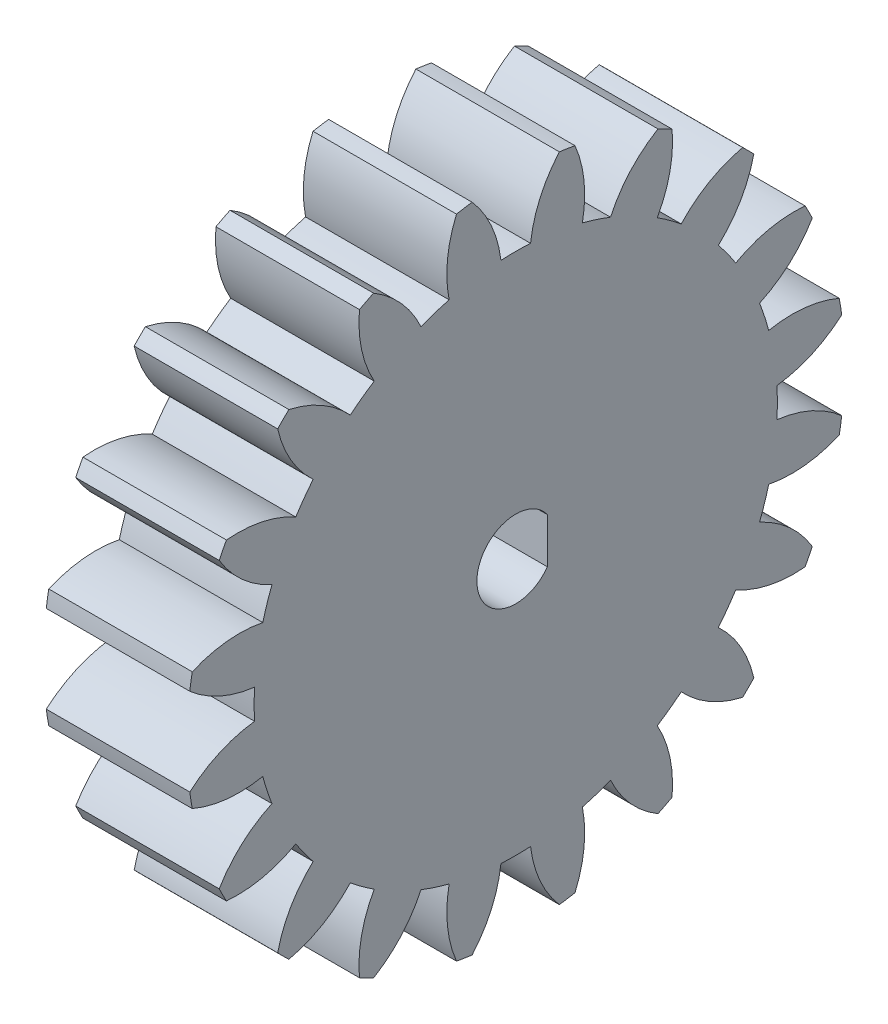
SolidWorks part; units mm, degrees
ref_plane "Plane1" through (0, 0, 0) normal (0, 0, 1) x (1, 0, 0)
ref_plane "Plane2" through (0, 0, 0) normal (0, 1, 0) x (1, 0, 0)
ref_plane "Plane3" through (0, 0, 0) normal (1, 0, 0) x (0, 0, -1)
other "Configuration Table"
sketch "HoldingSke" plane through (0, 0, 0) normal (0, 1, 0) x (1, 0, 0)
  line L0 (0, 0) -> (0.3759, -0.1368)
  line L1 (-15, 0) -> (100, 0) construction
  line L2 (0, 0) -> (-2.1039, 2.3779)
  line L3 (0, 0) -> (-11.863, 4.5341)
  line L4 (0, 0) -> (8.1152, 2.9537)
  line L5 (0, 0) -> (-46.8476, -17.4728)
  line L6 (0, 0) -> (-9.9476, -6.7116)
  line L7 (-2.1039, 2.3779) -> (8.6586, 51.2059)
  line L8 (-76.2, 54.61) -> (-76.1, 54.61)
  line L9 (-71.009, 38.7566) -> (-53.1078, 45.2721)
  line L10 (-76.2, 71.12) -> (104.1128, 71.12)
  line L11 (0, 0) -> (-12, 0)
  line L12 (-76.2, 101.6) -> (-76.113, 101.6)
  line L13 (24.9733, 27.94) -> (52.9518, 28.4284)
  line L14 (24.9733, 27.94) -> (24.9743, 27.94)
  line L15 (24.9733, 27.94) -> (100.4006, 29.5858)
  line L16 (-63.627, -2.5) -> (-12.827, -2.5)
  circle A0 centre (0, 0) radius 0.4
  circle A1 centre (0, 0) radius 21.874
  circle A2 centre (0, 0) radius 37.5
  circle A3 centre (0, 0) radius 0.4
  dimension "MHD" = 43.748
  dimension "Hub_dia" = 75
  dimension "Bore" = 0.8
  dimension "MBD" = 0.8
  dimension "Num_teeth" = 20
  dimension "Pitch" = 0.4
  dimension "Overall_len" = 50
  dimension "Show_teeth" = 20
  dimension "Thickness" = 12
  dimension "OAL" = 50.0001
  dimension "T_dim" = 0.1
  dimension "Ap" = 20
  dimension "H" = 19.05
  dimension "Pitch_radius" = 180.3128
  dimension "Width" = 12
  dimension "Backlash" = 0.087
  dimension "Addendum_fac" = 1
  dimension "Dedendum_fac" = 1.25
  dimension "Clearance_fac" = 0.25
  dimension "Dedendum_add" = 0.001
  dimension "Module" = 2.5
sketch "BasProSke" plane through (0, 0, 0) normal (0, 1, 0) x (1, 0, 0)
  line L0 (-10, 0) -> (60, 0) construction
  line L1 (0, 0) -> (0, 27.5)
  line L2 (0, 0) -> (12, 0)
  line L3 (12, 0) -> (12, 27.5)
  line L4 (12, 27.5) -> (0, 27.5)
  dimension "Thickness" = 12
  dimension "Diameter" = 55
revolve "Base-Revolve" add sketch "BasProSke" angle 360 about L0
sketch "TooCutSke" plane through (0, 0, 0) normal (1, 0, 0) x (0, 0, -1)
  line L1 (0, 0) -> (0, 107) construction
  line L2 (0, 0) -> (-2.1137, 24.9105) construction
  line L3 (0, 0) -> (-7.8012, 49.2549) construction
  line L4 (-2.1137, 24.9105) -> (-3.9006, 24.6275) construction
  arc A0 (1.2377, 21.839) -> (-1.2377, 21.839) centre (0, 0) ccw
  arc A1 (3.6672, 27.28) -> (-3.6672, 27.28) centre (0, 0) ccw
  circle A2 centre (0, 0) radius 25 construction
  circle A3 centre (0, 0) radius 23.4923 construction
  arc A4 (-1.2377, 21.839) -> (-3.6672, 27.28) centre (-11.1689, 20.6675) ccw
  arc A5 (3.6672, 27.28) -> (1.2377, 21.839) centre (11.1689, 20.6675) ccw
  dimension "Root_dia" = 43.748
  dimension "Overcut_dia" = 55.0508
  dimension "Pitch_dia" = 50
  dimension "Base_dia" = 46.9846
  dimension "Flank_rad" = 10
  dimension "Half_ang" = 9
  dimension "Half_CT" = 1.8092
extrude "ToothCut" cut sketch "TooCutSke" along normal through all
fillet "Breaks" [suppressed] radius 0.05
fillet "RootFillets" [suppressed] radius 0.626
pattern_circular "TeethCuts" count 20 every 18 about axis through (-10, 0, 0) along (1, 0, 0) of "ToothCut", "RootFillets", "Breaks"
sketch "HubNeaOneSke" plane through (0, 0, 0) normal (-1, 0, 0) x (0, 0, 1)
  circle A0 centre (0, 0) radius 21.874
  dimension "Diameter" = 43.748
extrude "HubNearOne" [suppressed] add sketch "HubNeaOneSke" along normal blind 38.0001
sketch "HubNeaBotSke" plane through (0, 0, 0) normal (-1, 0, 0) x (0, 0, 1)
  circle A0 centre (0, 0) radius 21.874
  dimension "Diameter" = 43.748
extrude "HubNearBoth" [suppressed] add sketch "HubNeaBotSke" along normal blind 19
ref_plane "FarPln" through (12, 0, 0) normal (1, 0, 0) x (0, 0, -1)
sketch "HubFarSke" plane through (12, 0, 0) normal (1, 0, 0) x (0, 0, -1)
  circle A0 centre (0, 0) radius 21.874
  dimension "Diameter" = 43.748
extrude "HubFar" [suppressed] add sketch "HubFarSke" along normal blind 19
sketch "BorSke" plane through (0, 0, 0) normal (1, 0, 0) x (0, 0, -1)
  circle A0 centre (0, 0) radius 0.4
  dimension "Diameter" = 0.8
extrude "Bore" cut sketch "BorSke" along normal mid plane 100.0001
sketch "KeySke" plane through (0, 0, 0) normal (1, 0, 0) x (0, 0, -1)
  line L0 (-0.05, 0) -> (-0.05, 0.5)
  line L1 (-0.05, 0.5) -> (0.05, 0.5)
  line L2 (0.05, 0.5) -> (0.05, 0)
  line L3 (0, 0) -> (0, 34) construction
  line L4 (-0.05, 0) -> (0.05, 0)
  dimension "Offset" = 0.5
  dimension "Width" = 0.1
extrude "Keyway" [suppressed] cut sketch "KeySke" along normal mid plane 100.0001
pattern_circular "Keyway2" [suppressed] count 2 every 90 about axis through (-10, 0, 0) along (1, 0, 0)
sketch "Çizim1" plane through (0, 0, 0) normal (-1, 0, 0) x (0, 0, 1)
  line L0 (-2.6439, 1.49) -> (-2.6439, -2.29)
  circle A0 centre (0, -0.4) radius 3.25
  circle A1 centre (0, 0) radius 0.4 construction
  dimension "D1" = 6.5
  dimension "D2" = 3.78
extrude "Kes-Ekstrüzyon1" cut sketch "Çizim1" against normal blind 100 contours L0 A0
equation "' \"Module@HoldingSke\" = 6.35"
equation "' \"Num_teeth@HoldingSke\" = 12"
equation "' \"Ap@HoldingSke\" =  20"
equation "' \"Ap@HoldingSke\" = 20"
equation "' \"Width@HoldingSke\" = 0.5 * 25.4"
equation "' \"Hub_dia@HoldingSke\"= 1 * 25.4"
equation "' \"Hub_dia@HoldingSke\" = 1 * 25.4"
equation "' \"Overall_len@HoldingSke\" = 1.0 * 25.4"
equation "' \"Bore@HoldingSke\" = 0.75 * 25.4"
equation "' \"T_dim@HoldingSke\" = 0.1 * 25.4"
equation "' \"Width@KeySke\" = 0.25 * 25.4"
equation "' \"Show_teeth@HoldingSke\" = 13"
equation "' \"Backlash@HoldingSke\" = 0.009 * 25.4"
equation "' \"Addendum_fac@HoldingSke\" = 1.0"
equation "' \"Dedendum_fac@HoldingSke\" = 1.25"
equation "' \"Dedendum_add@HoldingSke\" = 0.00005 * 25.4"
equation "' \"Clearance_fac@HoldingSke\" = 0.25"
equation "\"Pitch@HoldingSke\" = 1 / \"Module@HoldingSke\""
equation "\"Overcut_dia@TooCutSke\" = (\"Num_teeth@HoldingSke\" + 2 * \"Addendum_fac@HoldingSke\") / \"Pitch@HoldingSke\" + 0.002 * 25.4"
equation "\"Pitch_dia@TooCutSke\" = \"Num_teeth@HoldingSke\" / \"Pitch@HoldingSke\""
equation "\"Base_dia@TooCutSke\" = \"Num_teeth@HoldingSke\" / \"Pitch@HoldingSke\" * cos((\"Ap@HoldingSke\"  * 3.14159265 / 180))"
equation "\"Root_dia@TooCutSke\" = (\"Num_teeth@HoldingSke\" + 2) / \"Pitch@HoldingSke\" - 2 * (\"Addendum_fac@HoldingSke\" + \"Dedendum_fac@HoldingSke\") / \"Pitch@HoldingSke\" - \"Dedendum_add@HoldingSke\" * 2"
equation "\"Half_ang@TooCutSke\" = 180 / \"Num_teeth@HoldingSke\""
equation "\"Half_CT@TooCutSke\" = \"Num_teeth@HoldingSke\" / \"Pitch@HoldingSke\" * sin((3.14159265 / 2 / \"Num_teeth@HoldingSke\")) / 2 - 7 * \"Backlash@HoldingSke\" / 4"
equation "\"Flank_rad@TooCutSke\" = \"Num_teeth@HoldingSke\" / \"Pitch@HoldingSke\" / 5"
equation "\"Radius@RootFillets\" = \"Clearance_fac@HoldingSke\" / \"Pitch@HoldingSke\" + \"Dedendum_add@HoldingSke\""
equation "\"Break_rad@Breaks\" = 0.02 / \"Pitch@HoldingSke\""
equation "\"Thickness@HoldingSke\" = \"Width@HoldingSke\""
equation "\"OAL@HoldingSke\" = \"Thickness@HoldingSke\""
equation "\"MHD@HoldingSke\" = (\"Num_teeth@HoldingSke\" + 2) / \"Pitch@HoldingSke\" - 2 * (\"Addendum_fac@HoldingSke\" + \"Dedendum_fac@HoldingSke\")  / \"Pitch@HoldingSke\" - \"Dedendum_add@HoldingSke\" * 2"
equation "\"MBD@HoldingSke\" = (\"Num_teeth@HoldingSke\" + 2) / \"Pitch@HoldingSke\" - 2 * (\"Addendum_fac@HoldingSke\" + \"Dedendum_fac@HoldingSke\")  / \"Pitch@HoldingSke\" - \"Dedendum_add@HoldingSke\" * 2 - 0.002 * 25.4"
equation "\"MHD@HoldingSke\" = ((sgn( \"MHD@HoldingSke\" - \"Hub_dia@HoldingSke\" )-1)*( \"MHD@HoldingSke\" - \"Hub_dia@HoldingSke\" ))/-2+ \"Hub_dia@HoldingSke\""
equation "\"MBD@HoldingSke\" = ((sgn( \"MBD@HoldingSke\" - \"Bore@HoldingSke\" )-1)*( \"MBD@HoldingSke\" - \"Bore@HoldingSke\" ))/-2+ \"Bore@HoldingSke\""
equation "\"OAL@HoldingSke\" = ((sgn( \"OAL@HoldingSke\" - \"Overall_len@HoldingSke\" )+1)*( \"OAL@HoldingSke\" - \"Overall_len@HoldingSke\" ))/2 + \"Overall_len@HoldingSke\" + 0.000002 * 25.4"
equation "\"Num_teeth@TeethCuts\" = int( \"Show_teeth@HoldingSke\" ) + 1"
equation "\"Num_teeth@TeethCuts\" = ((sgn( \"Num_teeth@TeethCuts\" - \"Num_teeth@HoldingSke\" )-1)*( \"Num_teeth@TeethCuts\" - \"Num_teeth@HoldingSke\" ))/-2+ \"Num_teeth@HoldingSke\""
equation "\"Num_teeth@TeethCuts\" = ((sgn( \"Num_teeth@TeethCuts\" - 2.0)+1)*( \"Num_teeth@TeethCuts\" - 2.0))/2 +2.0"
equation "\"Angle@TeethCuts\" = 360.0 / \"Num_teeth@HoldingSke\""
equation "\"Diameter@BasProSke\" = (\"Num_teeth@HoldingSke\" + 2 * \"Addendum_fac@HoldingSke\") / \"Pitch@HoldingSke\""
equation "\"Thickness@BasProSke\"  = \"Thickness@HoldingSke\""
equation "' \"Fillet_rad@BasProSke\" =  \"Thickness@HoldingSke\" * 0.05"
equation "' \"Fillet_rad@BasProSke\" = \"Thickness@HoldingSke\" * 0.05"
equation "\"MHD@HoldingSke\" = ((sgn( \"MHD@HoldingSke\" - \"Root_dia@TooCutSke\" )-1)*( \"MHD@HoldingSke\" - \"Root_dia@TooCutSke\" ))/-2+ \"Root_dia@TooCutSke\""
equation "\"Diameter@HubNeaOneSke\" = \"MHD@HoldingSke\""
equation "\"Length@HubNearOne\" = \"OAL@HoldingSke\" - \"Thickness@BasProSke\""
equation "\"Diameter@HubNeaBotSke\" = \"MHD@HoldingSke\""
equation "\"Length@HubNearBoth\" = ( \"OAL@HoldingSke\" - \"Thickness@BasProSke\" ) / 2.0"
equation "\"Thickness@FarPln\" = \"Thickness@BasProSke\""
equation "\"Diameter@HubFarSke\" = \"MHD@HoldingSke\""
equation "\"Length@HubFar\" = ( \"OAL@HoldingSke\" - \"Thickness@BasProSke\" ) / 2.0"
equation "\"Diameter@BorSke\" = \"MBD@HoldingSke\""
equation "\"D1@Bore\" = \"OAL@HoldingSke\" * 2.0"
equation "\"D1@Keyway\" = \"OAL@HoldingSke\" * 2.0"
equation "\"Offset@KeySke\" = \"T_dim@HoldingSke\" + \"MBD@HoldingSke\" / 2.0"
